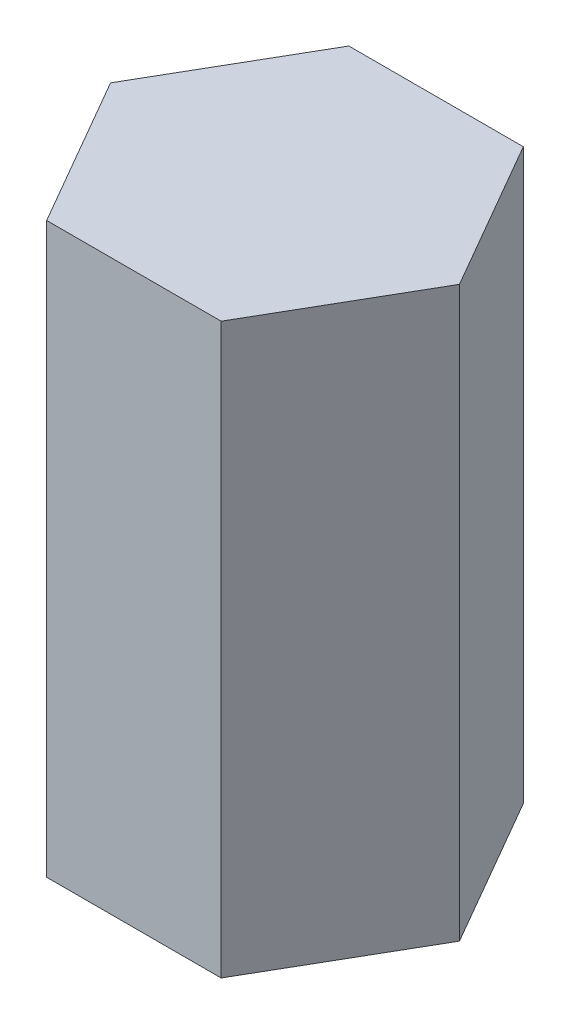
SolidWorks part; units mm, degrees
ref_plane "Front Plane" through (0, 0, 0) normal (0, 0, 1) x (1, 0, 0)
ref_plane "Top Plane" through (0, 0, 0) normal (0, 1, 0) x (1, 0, 0)
ref_plane "Right Plane" through (0, 0, 0) normal (1, 0, 0) x (0, 0, -1)
sketch "Sketch1" plane through (0, 0, 0) normal (0, 1, 0) x (1, 0, 0)
  line L0 (-55, 0) -> (55, 0) construction
  line L1 (4.9075, -8.5) -> (9.815, 0)
  line L2 (9.815, 0) -> (4.9075, 8.5)
  line L3 (4.9075, 8.5) -> (-4.9075, 8.5)
  line L4 (-4.9075, 8.5) -> (-9.815, 0)
  line L5 (-9.815, 0) -> (-4.9075, -8.5)
  line L6 (-4.9075, -8.5) -> (4.9075, -8.5)
  circle A0 centre (0, 0) radius 8.5 construction
  point P1 (9.4529, 2.6412)
  point P12 (0, 0)
  dimension "D1" = 17
extrude "Boss-Extrude1" add sketch "Sketch1" along normal blind 32
